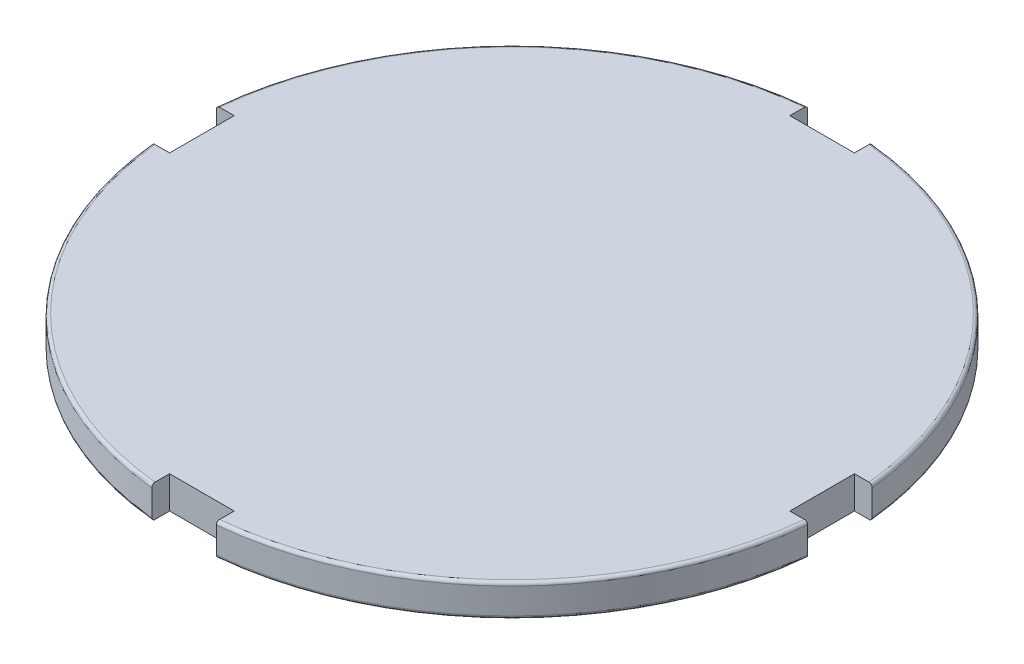
SolidWorks part; units mm, degrees
ref_plane "Front" through (0, 0, 0) normal (0, 0, 1) x (1, 0, 0)
ref_plane "Top" through (0, 0, 0) normal (0, 1, 0) x (1, 0, 0)
ref_plane "Right" through (0, 0, 0) normal (1, 0, 0) x (0, 0, -1)
sketch "Sketch2" plane through (0, 0, 0) normal (0, 1, 0) x (1, 0, 0)
  circle A0 centre (0, 0) radius 64.77
  dimension "D1" = 129.54
extrude "Boss-Extrude1" add sketch "Sketch2" along normal blind 6.35
fillet "Fillet1" radius 0.635 2 edges at (0, 0, 64.77) (0, 6.35, 64.77)
sketch "Sketch4" plane through (0, 0, 0) normal (0, -1, 0) x (1, 0, 0)
  line L0 (0, -75.0224) -> (0, 83.7175) construction
  line L1 (-82.7142, 0) -> (82.2683, 0) construction
  line L2 (74.911, 6.35) -> (74.911, -6.35)
  line L3 (0, -11.0767) -> (60.96, -11.0767) construction
  line L4 (74.911, -6.35) -> (60.96, -6.35)
  line L5 (74.911, 6.35) -> (60.96, 6.35)
  line L6 (60.96, 6.35) -> (60.96, -6.35)
  line L7 (6.35, -60.96) -> (-6.35, -60.96)
  line L8 (-6.35, -74.911) -> (-6.35, -60.96)
  line L9 (6.35, -74.911) -> (-6.35, -74.911)
  line L10 (6.35, -74.911) -> (6.35, -60.96)
  line L11 (-60.96, -6.35) -> (-60.96, 6.35)
  line L12 (-74.911, 6.35) -> (-60.96, 6.35)
  line L13 (-74.911, -6.35) -> (-74.911, 6.35)
  line L14 (-74.911, -6.35) -> (-60.96, -6.35)
  line L15 (-6.35, 60.96) -> (6.35, 60.96)
  line L16 (6.35, 74.911) -> (6.35, 60.96)
  line L17 (-6.35, 74.911) -> (6.35, 74.911)
  line L18 (-6.35, 74.911) -> (-6.35, 60.96)
  point P8 (74.911, 0)
  point P27 (0, 0)
  dimension "D1" = 6.35
  dimension "D2" = 60.96
  dimension "D3" = 4
extrude "Cut-Extrude1" cut sketch "Sketch4" against normal through all
